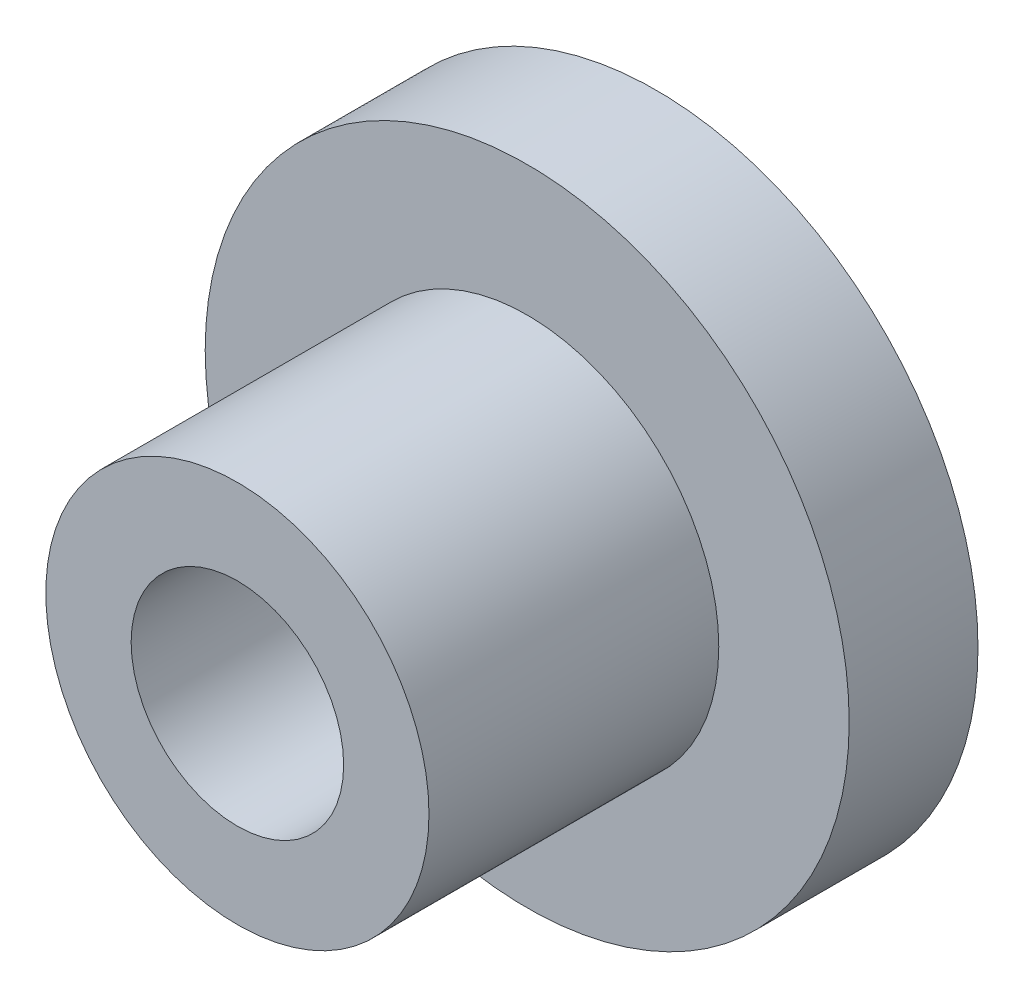
SolidWorks part; units mm, degrees
material "PET"
ref_plane "Plan de face" through (0, 0, 0) normal (0, 0, 1) x (1, 0, 0)
ref_plane "Plan de dessus" through (0, 0, 0) normal (0, 1, 0) x (1, 0, 0)
ref_plane "Plan de droite" through (0, 0, 0) normal (1, 0, 0) x (0, 0, -1)
sketch "Esquisse1" plane through (0, 0, 0) normal (0, 1, 0) x (1, 0, 0)
  line L0 (5, -2) -> (5, 0)
  line L1 (5, 0) -> (1.65, 0)
  line L2 (1.65, 0) -> (1.65, -6.5)
  line L3 (1.65, -6.5) -> (2.975, -6.5)
  line L4 (2.975, -6.5) -> (2.975, -2)
  line L5 (2.975, -2) -> (5, -2)
  line L6 (0, 0) -> (0, -6.5) construction
  dimension "D1" = 5.95
  dimension "D2" = 3.3
  dimension "D3" = 10
  dimension "D4" = 2
  dimension "D5" = 6.5
revolve "Révolution1" add sketch "Esquisse1" angle 360 about L6
